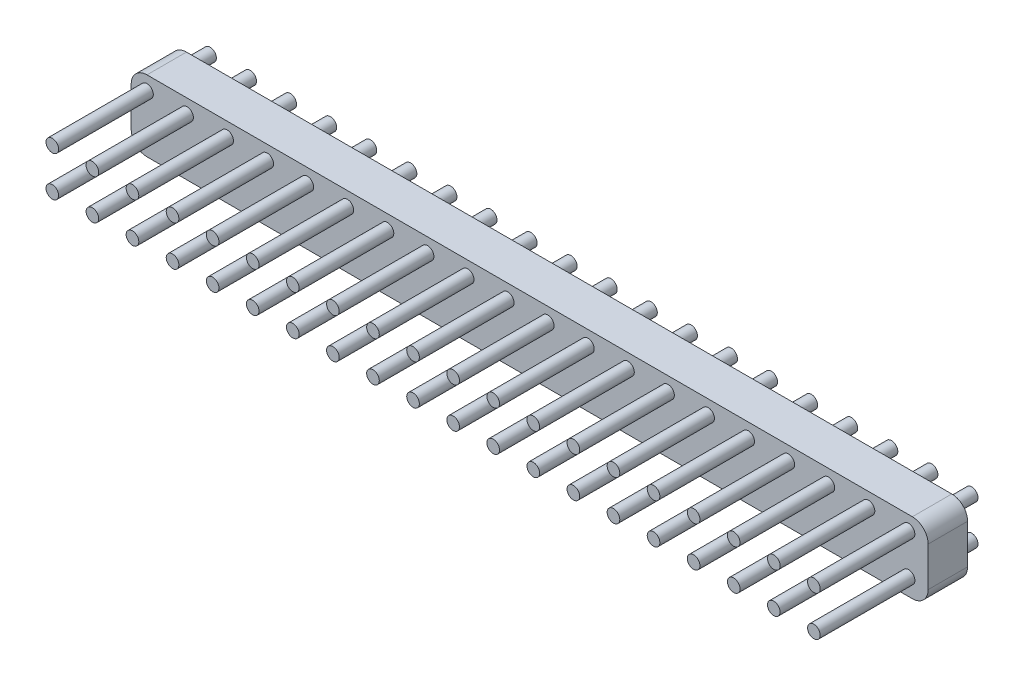
SolidWorks part; units mm, degrees
ref_plane "正面" through (0, 0, 0) normal (0, 0, 1) x (1, 0, 0)
ref_plane "平面" through (0, 0, 0) normal (0, 1, 0) x (1, 0, 0)
ref_plane "右側面" through (0, 0, 0) normal (1, 0, 0) x (0, 0, -1)
sketch "ｽｹｯﾁ1" plane through (0, 0, 0) normal (0, 0, 1) x (1, 0, 0)
  line L1 (-25.25, -2.25) -> (25.25, -2.25)
  line L2 (-25.25, -2.25) -> (-25.25, 2.25)
  line L3 (-25.25, 2.25) -> (25.25, 2.25)
  line L4 (25.25, -2.25) -> (25.25, 2.25)
  line L5 (-25.25, -2.25) -> (25.25, 2.25) construction
  line L6 (-25.25, 2.25) -> (25.25, -2.25) construction
  point P0 (0, 0)
  dimension "D1" = 50.5
  dimension "D2" = 4.5
extrude "ﾎﾞｽ - 押し出し1" add sketch "ｽｹｯﾁ1" along normal blind 2.5
sketch "ｽｹｯﾁ2" plane through (0, 0, 2.5) normal (0, 0, 1) x (1, 0, 0)
  line L0 (-25.25, 2.25) -> (-25.25, -2.25) construction
  circle A0 centre (-24.25, 1.37) radius 0.4
  circle A1 centre (-24.25, -1.17) radius 0.4
  point P6 (-25.25, 0)
  dimension "D1" = 0.8
  dimension "D2" = 0.8
  dimension "D3" = 2.54
  dimension "D4" = 1.37
  dimension "D5" = 1
extrude "ﾎﾞｽ - 押し出し2" add sketch "ｽｹｯﾁ2" along normal blind 6 and the other way blind 4
pattern_linear "直線ﾊﾟﾀｰﾝ2" count 20 spacing 2.54 along (1, 0, 0) of "ﾎﾞｽ - 押し出し2"
fillet "ﾌｨﾚｯﾄ1" radius 1 4 edges at (25.25, 2.25, 1.25) (25.25, -2.25, 1.25) (-25.25, 2.25, 1.25) (-25.25, -2.25, 1.25)
